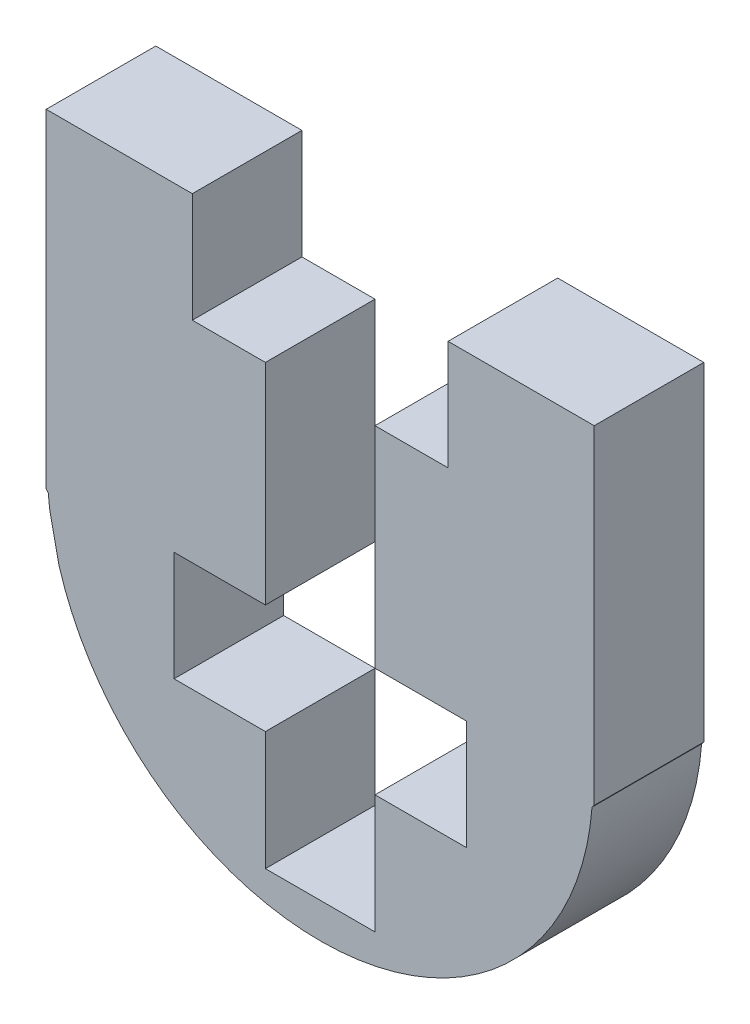
SolidWorks part; units mm, degrees
ref_plane "Alzado" through (0, 0, 0) normal (0, 0, 1) x (1, 0, 0)
ref_plane "Planta" through (0, 0, 0) normal (0, 1, 0) x (1, 0, 0)
ref_plane "Vista lateral" through (0, 0, 0) normal (1, 0, 0) x (0, 0, -1)
sketch "Croquis1" plane through (0, 0, 0) normal (0, 0, 1) x (1, 0, 0)
  line L0 (-5, -7.5) -> (-5, 1.5094) construction
  line L2 (-7.5, -0.5) -> (-7.5, 8.5)
  line L3 (-7.5, 8.5) -> (7.5, 8.5)
  line L4 (7.5, -0.5) -> (7.5, 8.5)
  line L5 (-5, -5.6667) -> (7.5, 8.5) construction
  line L6 (-7.5, 8.5) -> (7.5, -8.5) construction
  line L7 (3, -7.5) -> (3, 2.9864) construction
  line L8 (-3, -7.5) -> (-3, 2.9864) construction
  line L9 (0, 0) -> (0, 4.1652) construction
  line L10 (5, -7.5) -> (5, 1.5094) construction
  line L11 (-3, -4.4624) -> (-5, -3.5)
  line L12 (-5, -3.5) -> (-7.5, -0.5)
  line L13 (3, -4.4624) -> (5, -3.5)
  line L14 (5, -3.5) -> (7.5, -0.5)
  arc A0 (-3, -4.4624) -> (3, -4.4624) centre (0, -4.4624) ccw
  point P0 (0, 0)
  dimension "D1" = 15
  dimension "D2" = 17
  dimension "D3" = 5
  dimension "D5" = 3
extrude "Saliente-Extruir1" add sketch "Croquis1" along normal blind 3
sketch "Croquis2" plane through (0, 0, 3) normal (0, 0, 1) x (1, 0, 0)
  line L0 (0, 8.5) -> (0, -6.5) construction
  line L1 (7.5, 8.5) -> (-7.5, 8.5) construction
  line L2 (1.5, 8.5) -> (-1.5, 8.5)
  line L3 (-1.5, 8.5) -> (-1.5, -0.25)
  line L4 (-1.5, -0.25) -> (-4, -0.25)
  line L5 (-4, -0.25) -> (-4, -3.25)
  line L6 (-4, -3.25) -> (-1.5, -3.25)
  line L7 (-1.5, -3.25) -> (-1.5, -6.5)
  line L8 (-1.5, -6.5) -> (1.5, -6.5)
  line L9 (1.5, -3.25) -> (1.5, -6.5)
  line L10 (4, -3.25) -> (1.5, -3.25)
  line L11 (4, -0.25) -> (4, -3.25)
  line L12 (1.5, -0.25) -> (4, -0.25)
  line L13 (1.5, 8.5) -> (1.5, -0.25)
  dimension "D1" = 15
  dimension "D2" = 8.75
  dimension "D3" = 2.5
  dimension "D4" = 2.5
  dimension "D5" = 3
  dimension "D6" = 1.5
extrude "Cortar-Extruir1" cut sketch "Croquis2" against normal blind 10
sketch "Croquis3" plane through (0, 0, 3) normal (0, 0, 1) x (1, 0, 0)
  line L0 (-7.5, 8.5) -> (-7.5, -0.5) construction
  line L1 (-1.5, 8.5) -> (-3.5, 8.5)
  line L2 (-1.5, 8.5) -> (-1.5, 5.5)
  line L3 (-1.5, 5.5) -> (-3.5, 5.5)
  line L4 (-3.5, 8.5) -> (-3.5, 5.5)
  line L5 (0, 0) -> (0, 3.2703) construction
  line L6 (1.5, 5.5) -> (3.5, 5.5)
  line L7 (3.5, 8.5) -> (3.5, 5.5)
  line L8 (1.5, 8.5) -> (3.5, 8.5)
  line L9 (1.5, 8.5) -> (1.5, 5.5)
  dimension "D1" = 3
  dimension "D2" = 4
extrude "Cortar-Extruir2" cut sketch "Croquis3" against normal blind 10
sketch "Croquis5" plane through (0, 0, 3) normal (0, 0, 1) x (1, 0, 0)
  line L0 (-7.5, -0.5) -> (-7.1465, -2.1482)
  line L1 (7.5, -0.5) -> (7.4405, -0.5714)
  line L23 (-1.5, 5.5) -> (-3.5, 5.5)
  line L24 (-3.5, 5.5) -> (-3.5, 8.5)
  line L25 (-3.5, 8.5) -> (-7.5, 8.5)
  line L26 (-7.5, 8.5) -> (-7.5, -0.5)
  line L27 (-7.5, -0.5) -> (-5, -3.5)
  line L28 (-5, -3.5) -> (-3, -4.4624)
  line L29 (3, -4.4624) -> (5, -3.5)
  line L30 (5, -3.5) -> (7.5, -0.5)
  line L31 (7.5, -0.5) -> (7.5, 8.5)
  line L32 (7.5, 8.5) -> (3.5, 8.5)
  line L33 (3.5, 8.5) -> (3.5, 5.5)
  line L34 (3.5, 5.5) -> (1.5, 5.5)
  line L35 (1.5, 5.5) -> (1.5, -0.25)
  line L36 (1.5, -0.25) -> (4, -0.25)
  line L37 (4, -0.25) -> (4, -3.25)
  line L38 (4, -3.25) -> (1.5, -3.25)
  line L39 (1.5, -3.25) -> (1.5, -6.5)
  line L40 (1.5, -6.5) -> (-1.5, -6.5)
  line L41 (-1.5, -6.5) -> (-1.5, -3.25)
  line L42 (-1.5, -3.25) -> (-4, -3.25)
  line L43 (-4, -3.25) -> (-4, -0.25)
  line L44 (-4, -0.25) -> (-1.5, -0.25)
  line L45 (-1.5, -0.25) -> (-1.5, 5.5)
  line L46 (-1.5, 5.5) -> (-3.5, 5.5)
  line L47 (-3.5, 5.5) -> (-3.5, 8.5)
  line L48 (-3.5, 8.5) -> (-7.5, 8.5)
  line L49 (-7.5, 8.5) -> (-7.5, -0.5)
  line L50 (-7.5, -0.5) -> (-7.4405, -0.5714)
  line L53 (7.4405, -0.5714) -> (7.5, -0.5)
  line L54 (7.5, -0.5) -> (7.5, 8.5)
  line L55 (7.5, 8.5) -> (3.5, 8.5)
  line L56 (3.5, 8.5) -> (3.5, 5.5)
  line L57 (3.5, 5.5) -> (1.5, 5.5)
  line L58 (1.5, 5.5) -> (1.5, -0.25)
  line L59 (1.5, -0.25) -> (4, -0.25)
  line L60 (4, -0.25) -> (4, -3.25)
  line L61 (4, -3.25) -> (1.5, -3.25)
  line L62 (1.5, -3.25) -> (1.5, -6.5)
  line L63 (1.5, -6.5) -> (-1.5, -6.5)
  line L64 (-1.5, -6.5) -> (-1.5, -3.25)
  line L65 (-1.5, -3.25) -> (-4, -3.25)
  line L66 (-4, -3.25) -> (-4, -0.25)
  line L67 (-4, -0.25) -> (-1.5, -0.25)
  line L68 (-1.5, -0.25) -> (-1.5, 5.5)
  arc A0 (-7.4405, -0.5714) -> (7.4405, -0.5714) centre (0, 0) ccw
  arc A2 (-3, -4.4624) -> (3, -4.4624) centre (0, -4.4624) ccw
  line M30 (-7.5, -0.5) -> (-5, -3.5)
  line M31 (-5, -3.5) -> (-3, -4.4624)
  arc M32 (-3, -4.4624) -> (3, -4.4624) centre (0, -4.4624) ccw
  line M33 (3, -4.4624) -> (5, -3.5)
  line M34 (5, -3.5) -> (7.5, -0.5)
  dimension "D1" = 0
extrude "Saliente-Extruir2" add sketch "Croquis5" against normal blind 3 contours A0 L0 M30 M32 M31 | A0 M32 M34 M33
